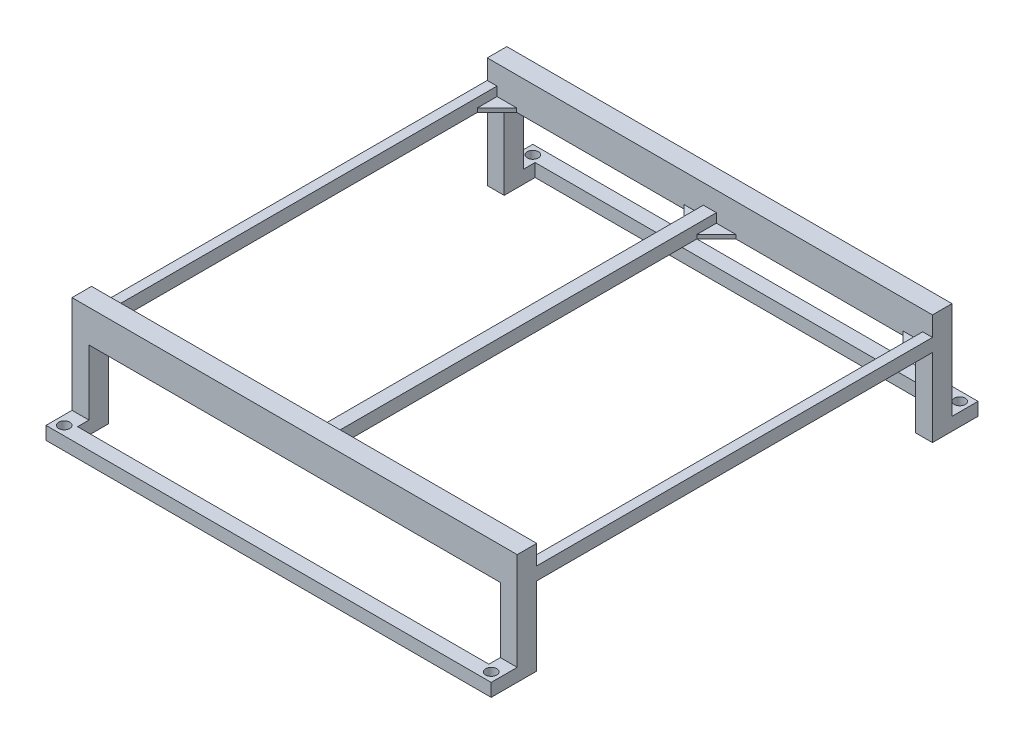
SolidWorks part; units mm, degrees
ref_plane "Front Plane" through (0, 0, 0) normal (0, 0, 1) x (1, 0, 0)
ref_plane "Top Plane" through (0, 0, 0) normal (0, 1, 0) x (1, 0, 0)
ref_plane "Right Plane" through (0, 0, 0) normal (1, 0, 0) x (0, 0, -1)
sketch "Sketch1" plane through (0, 0, 0) normal (0, 1, 0) x (1, 0, 0)
  line L0 (-55, 0) -> (55, 0) construction
  line L1 (-171, 11.25) -> (171, 11.25)
  line L3 (-158, 0) -> (158, 0)
  line L4 (171, 11.25) -> (171, 0)
  line L8 (-171, -13.75) -> (-158, -13.75)
  line L9 (-158, -13.75) -> (-158, 0)
  line L10 (0, -55) -> (0, 55) construction
  line L11 (171, -13.75) -> (158, -13.75)
  line L12 (158, -13.75) -> (158, 0)
  line L13 (171, 0) -> (171, -13.75)
  line L14 (-164, 4.25) -> (-164, 11.25) construction
  line L15 (-164, 4.25) -> (-171, 4.25) construction
  line L19 (-171, 11.25) -> (-171, -13.75)
  circle A0 centre (-164, 4.25) radius 4.25
  circle A1 centre (164, 4.25) radius 4.25
  point P6 (0, 0)
  dimension "D2" = 8.5
  dimension "D1" = 342
  dimension "D3" = 316
  dimension "D4" = 25
  dimension "D5" = 7
extrude "Boss-Extrude1" add sketch "Sketch1" along normal blind 10
sketch "Sketch2" plane through (0, 0, 13.75) normal (0, 0, 1) x (1, 0, 0)
  line L0 (-171, 0) -> (-171, 85)
  line L1 (-171, 10) -> (-171, 0) construction
  line L2 (-171, 85) -> (171, 85)
  line L3 (171, 85) -> (171, 0)
  line L4 (171, 10) -> (171, 0) construction
  line L5 (-171, 0) -> (-158, 0)
  line L6 (-158, 0) -> (-158, 60)
  line L7 (-158, 60) -> (158, 60)
  line L8 (158, 60) -> (158, 0)
  line L9 (-15.9953, 60) -> (-15.9953, 85) construction
  line L10 (-158, 52.4694) -> (-171, 52.4694) construction
  line L11 (55, 0) -> (-55, 0) construction
  line L12 (158, 0) -> (171, 0)
  line L16 (158, 0) -> (171, 0)
  line L17 (171, 0) -> (171, 10)
  line L18 (171, 10) -> (158, 10)
  line L19 (158, 10) -> (158, 0)
  line L21 (171, 0) -> (171, 10)
  line L23 (158, 10) -> (158, 0)
  dimension "D1" = 60
  dimension "D2" = 25
  dimension "D3" = 0
extrude "Boss-Extrude2" add sketch "Sketch2" against normal blind 5 and the other way blind 10
sketch "Sketch3" plane through (0, 0, 23.75) normal (0, 0, 1) x (1, 0, 0)
  line L0 (171, 85) -> (171, 0) construction
  line L1 (-171, 70) -> (171, 70)
  line L2 (-171, 70) -> (-171, 60)
  line L3 (-171, 60) -> (171, 60)
  line L4 (171, 70) -> (171, 60)
  line L5 (-158, 60) -> (158, 60) construction
  line L6 (-171, 0) -> (-171, 85) construction
  dimension "D1" = 10
extrude "Boss-Extrude3" add sketch "Sketch3" along normal blind 304
sketch "Sketch4" plane through (0, 85, 0) normal (0, 1, 0) x (1, 0, 0)
  line L2 (-171, -23.75) -> (171, -23.75) construction
  line L3 (-163.5, -23.75) -> (-5, -23.75)
  line L4 (-163.5, -23.75) -> (-163.5, -34.75)
  line L5 (-163.5, -327.75) -> (-5, -327.75)
  line L6 (163.5, -23.75) -> (163.5, -51.4723)
  line L8 (-163.5, -80.765) -> (-171, -80.765) construction
  line L9 (-171, -327.75) -> (-171, -23.75) construction
  line L10 (163.5, -70.9551) -> (171, -70.9551) construction
  line L11 (171, -327.75) -> (171, -23.75) construction
  line L12 (-5, -68.9608) -> (0, -68.9608) construction
  line L13 (171, -327.75) -> (-171, -327.75) construction
  line L14 (-163.5, -39.75) -> (-163.5, -327.75)
  line L19 (163.5, -51.4723) -> (163.5, -327.75)
  line L20 (5, -23.75) -> (163.5, -23.75)
  line L25 (43.2116, -39.75) -> (43.2116, -23.75) construction
  line L27 (-5, -23.75) -> (-5, -327.75)
  line L28 (5, -39.75) -> (5, -327.75)
  line L30 (5, -327.75) -> (163.5, -327.75)
  line L32 (5, -39.75) -> (5, -23.75)
  line L33 (-163.5, -34.75) -> (-163.5, -39.75)
  line L34 (171, -23.75) -> (-171, -23.75) construction
  line L35 (0, -55) -> (0, 55) construction
  line L36 (0, -68.9608) -> (5, -68.9608) construction
  dimension "D1" = 5
  dimension "D4" = 7.5
extrude "Cut-Extrude1" cut sketch "Sketch4" against normal up to next
ref_plane "Plane1" through (0, 0, 175.75) normal (0, 0, -1) x (-1, 0, 0)
mirror "Mirror3" about plane through (0, 0, 175.75) normal (0, 0, -1) of "Boss-Extrude2", "Boss-Extrude1"
mirror "Mirror4" about plane through (0, 0, 175.75) normal (0, 0, -1) of "Boss-Extrude1"
ref_plane "Plane2" through (0, 60, 0) normal (0, -1, 0) x (-1, 0, 0)
sketch "Sketch7" plane through (0, 60, 0) normal (0, -1, 0) x (-1, 0, 0)
  line L6 (-163.5, -23.75) -> (-148.5, -23.75)
  line L7 (-158, -23.75) -> (-171, -23.75) construction
  line L8 (-163.5, -23.75) -> (-163.5, -327.75) construction
  line L9 (-5, -23.75) -> (-158, -23.75) construction
  line L10 (-148.5, -23.75) -> (-163.5, -38.75)
  line L11 (-163.5, -38.75) -> (-163.5, -23.75)
  line L12 (-5, -23.75) -> (-20, -23.75)
  line L13 (-20, -23.75) -> (-5, -38.75)
  line L14 (-5, -327.75) -> (-5, -23.75) construction
  line L15 (-5, -38.75) -> (-5, -23.75)
  dimension "D1" = 15
extrude "Boss-Extrude4" add sketch "Sketch7" against normal blind 3
mirror "Mirror5" about plane through (0, 0, 175.75) normal (0, 0, -1) of "Boss-Extrude4" second plane through (0, 0, 0) second plane normal (1, 0, 0)
